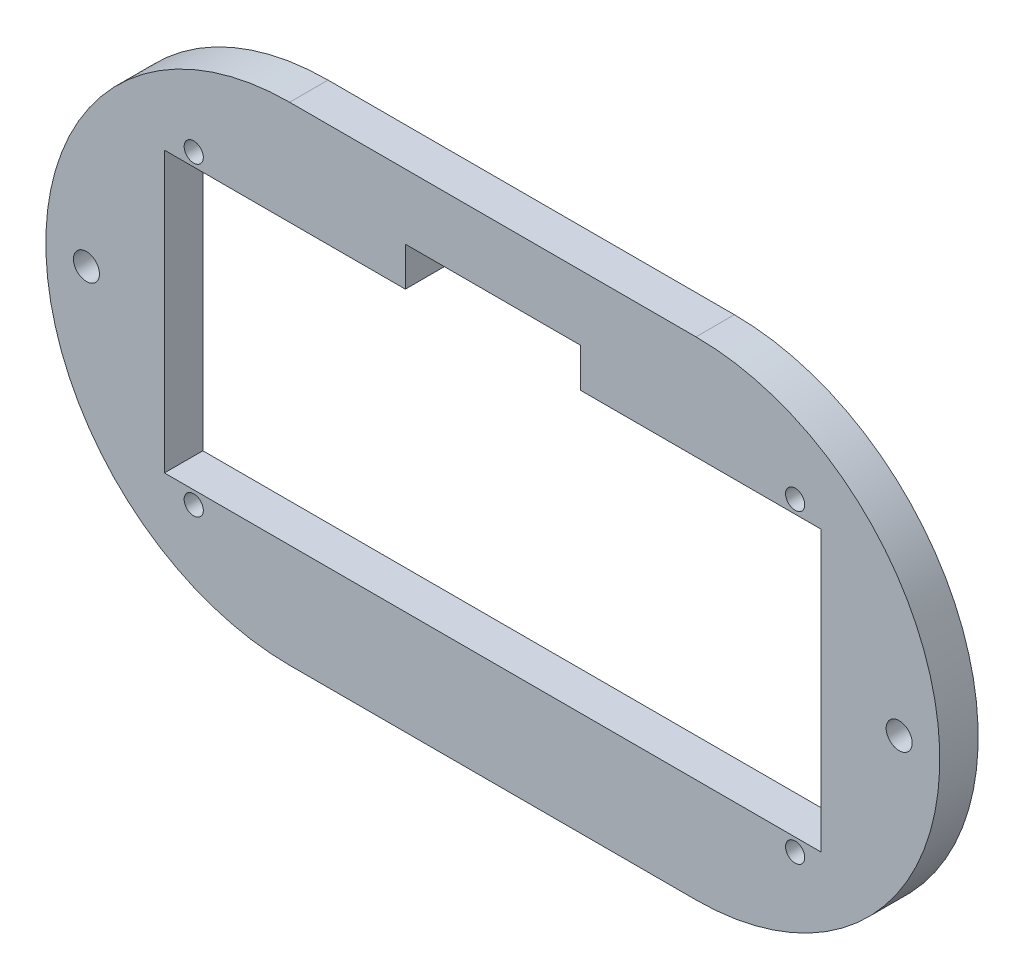
SolidWorks part; units mm, degrees
ref_plane "Front Plane" through (0, 0, 0) normal (0, 0, 1) x (1, 0, 0)
ref_plane "Top Plane" through (0, 0, 0) normal (0, 1, 0) x (1, 0, 0)
ref_plane "Right Plane" through (0, 0, 0) normal (1, 0, 0) x (0, 0, -1)
sketch "Sketch1" plane through (0, 0, 0) normal (0, 0, 1) x (1, 0, 0)
  line L0 (25.4, 29.718) -> (25.4, -8.382) construction
  line L1 (0, 0) -> (50.8, 0)
  line L2 (0, 0) -> (0, 21.336)
  line L3 (0, 21.336) -> (50.8, 21.336)
  line L4 (50.8, 0) -> (50.8, 21.336)
  line L5 (9.525, -8.382) -> (41.275, -8.382)
  line L7 (9.525, 29.718) -> (41.275, 29.718)
  line L9 (25.4, 10.668) -> (0, 10.668) construction
  line L10 (20.32, 23.368) -> (22.86, 23.368) construction
  line L11 (2.032, 22.606) -> (49.022, 22.606) construction
  line L12 (2.032, 22.606) -> (2.032, -1.27) construction
  line L13 (2.032, -1.27) -> (49.022, -1.27) construction
  line L14 (49.022, 22.606) -> (49.022, -1.27) construction
  line L15 (0, 24.638) -> (50.8, 24.638) construction
  line L16 (0, 24.638) -> (0, -3.302) construction
  line L17 (0, -3.302) -> (50.8, -3.302) construction
  line L18 (50.8, 24.638) -> (50.8, -3.302) construction
  line L19 (22.86, 23.368) -> (25.4, 23.368) construction
  line L20 (25.4, 23.368) -> (27.94, 23.368) construction
  line L21 (27.94, 23.368) -> (30.48, 23.368) construction
  circle A0 centre (-6.35, 10.668) radius 1.016
  circle A1 centre (57.15, 10.668) radius 1.016
  circle A2 centre (-6.35, 10.668) radius 3.175
  circle A3 centre (57.15, 10.668) radius 3.175
  circle A4 centre (2.032, 22.606) radius 1.1
  circle A5 centre (49.022, 22.606) radius 1.1
  circle A6 centre (2.032, -1.27) radius 1.1
  circle A7 centre (49.022, -1.27) radius 1.1
  arc A8 (9.525, 29.718) -> (9.525, -8.382) centre (9.525, 10.668) ccw
  arc A9 (41.275, 29.718) -> (41.275, -8.382) centre (41.275, 10.668) cw
  circle A10 centre (25.4, 23.368) radius 0.4826
  circle A11 centre (27.94, 23.368) radius 0.4826
  circle A12 centre (30.48, 23.368) radius 0.4826
  circle A13 centre (22.86, 23.368) radius 0.4826
  circle A14 centre (20.32, 23.368) radius 0.4826
  point P40 (25.4, 21.336)
  dimension "D2" = 2.032
  dimension "D3" = 6.35
  dimension "D6" = 2.2
  dimension "D14" = 69.85
  dimension "D15" = 0.9652
  dimension "D1" = 63.5
  dimension "D4" = 50.8
  dimension "D5" = 2.032
  dimension "D7" = 2.032
  dimension "D8" = 3.302
  dimension "D9" = 24.638
  dimension "D10" = 25.908
  dimension "D11" = 27.94
  dimension "D12" = 49.022
  dimension "D13" = 38.1
  dimension "D16" = 1.27
  dimension "D17" = 2.54
sketch "Sketch3" plane through (0, 0, 0) normal (0, 0, 1) x (1, 0, 0)
  line L0 (9.525, -8.382) -> (41.275, -8.382) construction
  line L1 (9.525, 29.718) -> (41.275, 29.718) construction
  line L2 (9.525, -8.382) -> (41.275, -8.382)
  line L3 (9.525, 29.718) -> (41.275, 29.718)
  line L8 (0, 24.638) -> (50.8, 24.638) construction
  line L9 (18.5674, 24.638) -> (32.2326, 24.638)
  line L10 (18.5674, 24.638) -> (18.5674, 21.59)
  line L12 (-0.254, -0.254) -> (51.054, -0.254)
  line L13 (51.054, -0.254) -> (51.054, 21.59)
  line L14 (51.054, 21.59) -> (-0.254, 21.59)
  line L15 (-0.254, 21.59) -> (-0.254, -0.254)
  line L16 (-0.254, -0.254) -> (51.054, -0.254)
  line L17 (51.054, -0.254) -> (51.054, 21.59)
  line L18 (51.054, 21.59) -> (32.2326, 21.59)
  line L19 (-0.254, 21.59) -> (-0.254, -0.254)
  line L20 (32.2326, 24.638) -> (32.2326, 21.59)
  line L21 (18.5674, 21.59) -> (-0.254, 21.59)
  circle A0 centre (57.15, 10.668) radius 1.016 construction
  circle A1 centre (-6.35, 10.668) radius 1.016 construction
  arc A2 (41.275, -8.382) -> (41.275, 29.718) centre (41.275, 10.668) ccw construction
  arc A3 (9.525, 29.718) -> (9.525, -8.382) centre (9.525, 10.668) ccw construction
  circle A4 centre (57.15, 10.668) radius 1.016
  circle A5 centre (-6.35, 10.668) radius 1.016
  arc A6 (41.275, -8.382) -> (41.275, 29.718) centre (41.275, 10.668) ccw
  arc A7 (9.525, 29.718) -> (9.525, -8.382) centre (9.525, 10.668) ccw
  circle A8 centre (2.032, 22.606) radius 0.75
  circle A9 centre (2.032, -1.27) radius 0.75
  circle A10 centre (49.022, -1.27) radius 0.75
  circle A11 centre (49.022, 22.606) radius 0.75
  circle A29 centre (20.32, 23.368) radius 0.4826 construction
  circle A30 centre (30.48, 23.368) radius 0.4826 construction
  dimension "D1" = 1.5
  dimension "D3" = 1.27
  dimension "D4" = 1.27
  dimension "D2" = 0.254
extrude "Boss-Extrude1" add sketch "Sketch3" along normal blind 3
sketch "Sketch4" [suppressed] plane through (0, 0, 0) normal (0, 0, 1) x (1, 0, 0)
  line L4 (9.525, -8.382) -> (41.275, -8.382) construction
  line L5 (9.525, 29.718) -> (41.275, 29.718) construction
  line L6 (9.525, -8.382) -> (41.275, -8.382)
  line L7 (9.525, 29.718) -> (41.275, 29.718)
  line L8 (-0.254, -0.254) -> (51.054, -0.254)
  line L9 (51.054, -0.254) -> (51.054, 21.59)
  line L10 (51.054, 21.59) -> (-0.254, 21.59)
  line L11 (-0.254, 21.59) -> (-0.254, -0.254)
  line L12 (-0.254, -0.254) -> (51.054, -0.254)
  line L13 (51.054, -0.254) -> (51.054, 21.59)
  line L14 (51.054, 21.59) -> (-0.254, 21.59)
  line L15 (-0.254, 21.59) -> (-0.254, -0.254)
  arc A0 (41.275, -8.382) -> (41.275, 29.718) centre (41.275, 10.668) ccw construction
  arc A1 (9.525, 29.718) -> (9.525, -8.382) centre (9.525, 10.668) ccw construction
  arc A2 (41.275, -8.382) -> (41.275, 29.718) centre (41.275, 10.668) ccw
  arc A3 (9.525, 29.718) -> (9.525, -8.382) centre (9.525, 10.668) ccw
  circle A4 centre (-6.35, 10.668) radius 1.5875
  circle A5 centre (57.15, 10.668) radius 1.5875
  dimension "D2" = 3.175
  dimension "D1" = 0.254
extrude "Boss-Extrude2" [suppressed] add sketch "Sketch4" along normal blind 3
sketch "Sketch5" [suppressed] plane through (0, 0, 3) normal (0, 0, 1) x (1, 0, 0)
  circle A0 centre (-6.35, 10.668) radius 2.54
  circle A1 centre (57.15, 10.668) radius 2.54
  dimension "D1" = 5.08
extrude "Cut-Extrude1" [suppressed] cut sketch "Sketch5" against normal blind 2
fillet "Fillet1" [suppressed] radius 2.54
